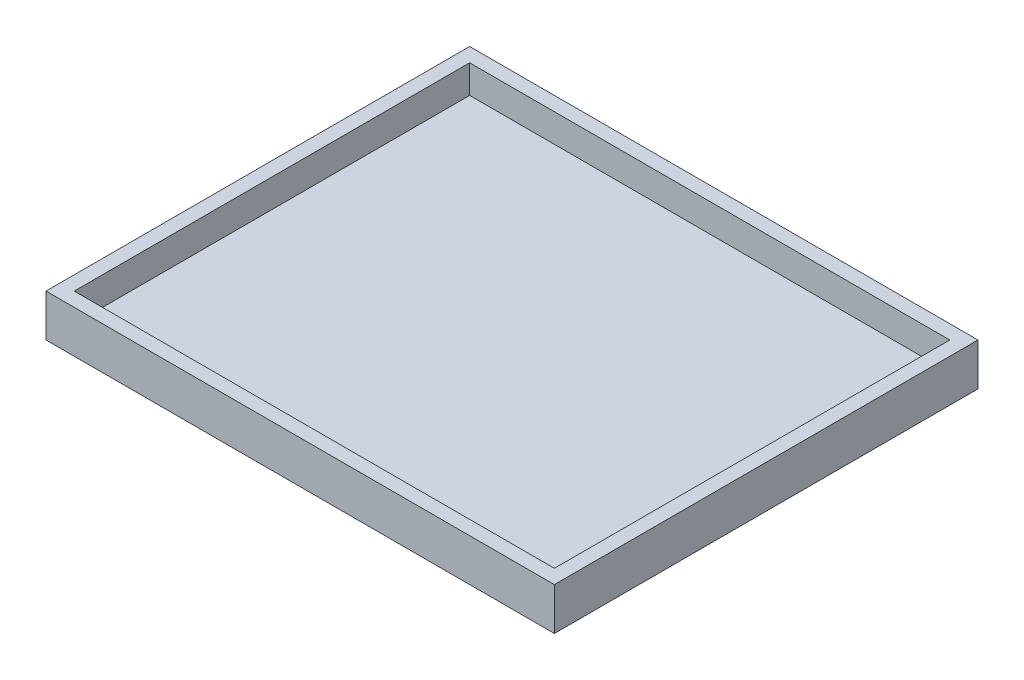
SolidWorks part; units mm, degrees
ref_plane "Front Plane" through (0, 0, 0) normal (0, 0, 1) x (1, 0, 0)
ref_plane "Top Plane" through (0, 0, 0) normal (0, 1, 0) x (1, 0, 0)
ref_plane "Right Plane" through (0, 0, 0) normal (1, 0, 0) x (0, 0, -1)
sketch "Sketch1" plane through (0, 0, 0) normal (0, 1, 0) x (1, 0, 0)
  line L1 (-45.0816, 7.0962) -> (46.3584, 7.0962)
  line L2 (-45.0816, 7.0962) -> (-45.0816, -69.1038)
  line L3 (-45.0816, -69.1038) -> (46.3584, -69.1038)
  line L4 (46.3584, 7.0962) -> (46.3584, -69.1038)
  dimension "D1" = 91.44
  dimension "D2" = 76.2
extrude "Boss-Extrude1" add sketch "Sketch1" along normal blind 7.62
sketch "Sketch2" plane through (0, 7.62, 0) normal (0, 1, 0) x (1, 0, 0)
  line L0 (46.3584, 7.0962) -> (-45.0816, 7.0962) construction
  line L1 (-42.5416, 4.5562) -> (43.8184, 4.5562)
  line L2 (-42.5416, 4.5562) -> (-42.5416, -66.5638)
  line L3 (-42.5416, -66.5638) -> (43.8184, -66.5638)
  line L4 (43.8184, 4.5562) -> (43.8184, -66.5638)
  line L5 (-45.0816, 7.0962) -> (-45.0816, -69.1038) construction
  dimension "D1" = 86.36
  dimension "D2" = 71.12
  dimension "D3" = 2.54
  dimension "D4" = 2.54
extrude "Cut-Extrude3" cut sketch "Sketch2" against normal blind 5.08
